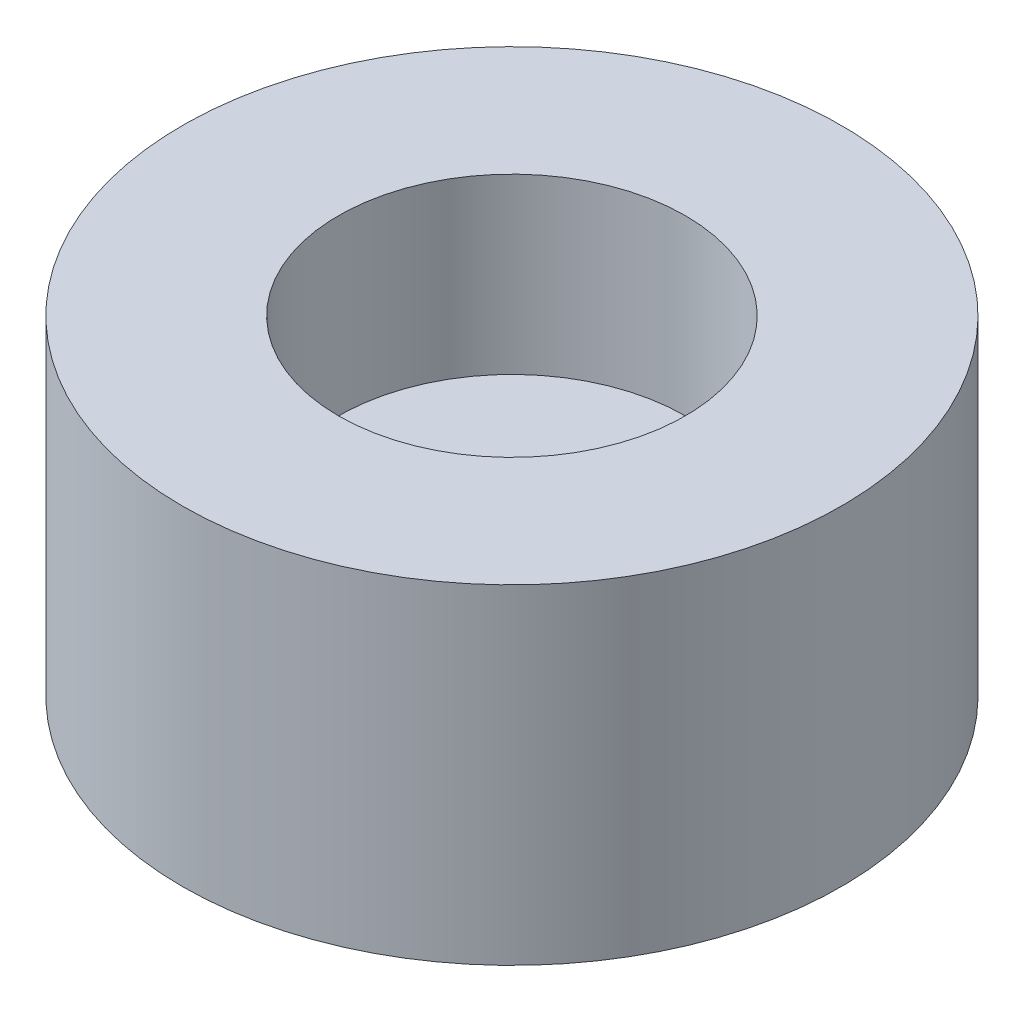
SolidWorks part; units mm, degrees
ref_plane "Front Plane" through (0, 0, 0) normal (0, 0, 1) x (1, 0, 0)
ref_plane "Top Plane" through (0, 0, 0) normal (0, 1, 0) x (1, 0, 0)
ref_plane "Right Plane" through (0, 0, 0) normal (1, 0, 0) x (0, 0, -1)
sketch "Sketch1" plane through (0, 0, 0) normal (0, 1, 0) x (1, 0, 0)
  circle A0 centre (0, 0) radius 19
  dimension "D1" = 38
extrude "Boss-Extrude1" add sketch "Sketch1" along normal blind 19
sketch "Sketch2" plane through (0, 19, 0) normal (0, 1, 0) x (1, 0, 0)
  circle A0 centre (0, 0) radius 10
  dimension "D1" = 20
extrude "Cut-Extrude1" cut sketch "Sketch2" against normal blind 10
sketch "Sketch3" plane through (0, 9, 0) normal (0, 1, 0) x (1, 0, 0)
  circle A0 centre (0, 0) radius 3.5
  dimension "D1" = 7
extrude "Cut-Extrude2" cut sketch "Sketch3" against normal up to surface (9 mm away) up to face at (0, 0, 19)
fillet "Fillet1" [suppressed] radius 2
